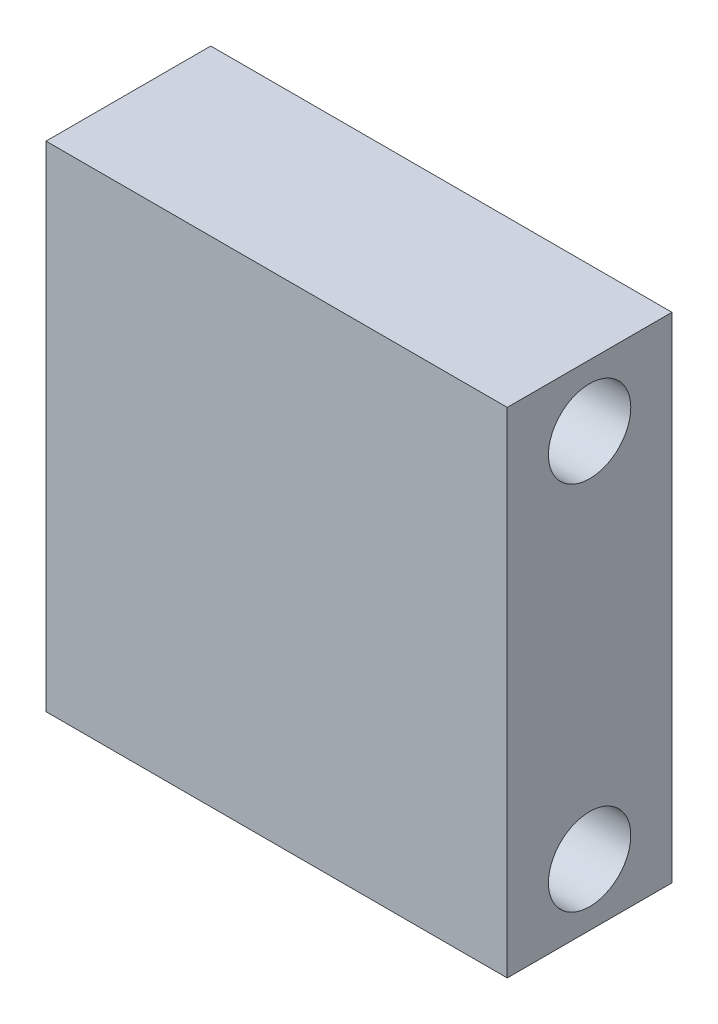
SolidWorks part; units mm, degrees
ref_plane "Front Plane" through (0, 0, 0) normal (0, 0, 1) x (1, 0, 0)
ref_plane "Top Plane" through (0, 0, 0) normal (0, 1, 0) x (1, 0, 0)
ref_plane "Right Plane" through (0, 0, 0) normal (1, 0, 0) x (0, 0, -1)
sketch "Sketch1" plane through (0, 0, 0) normal (1, 0, 0) x (0, 0, -1)
  line L0 (0, -22.5) -> (0, 22.5) construction
  line L1 (-10, 30) -> (10, 30)
  line L2 (-10, 30) -> (-10, -30)
  line L3 (-10, -30) -> (10, -30)
  line L4 (10, 30) -> (10, -30)
  line L5 (-10, 30) -> (10, -30) construction
  line L6 (-10, -30) -> (10, 30) construction
  line L7 (-10, 0) -> (10, 0) construction
  circle A0 centre (0, 22.5) radius 5
  circle A1 centre (0, -22.5) radius 5
  point P0 (0, 0)
  point P12 (0, 0)
  point P14 (4.7815, 23.9619)
  dimension "D3" = 10
  dimension "D1" = 20
  dimension "D2" = 60
  dimension "D4" = 45
extrude "Boss-Extrude1" add sketch "Sketch1" along normal blind 56
sketch "Sketch2" plane through (0, 0, -10) normal (0, 0, 1) x (1, 0, 0)
  line L0 (28, 30) -> (28, -90) construction
  line L1 (56, 30) -> (0, 30) construction
  dimension "D1" = 120
equation "\"X-ROD-SPACING\"=45"
equation "\"Y-ROD-SPACING\"=75"
equation "\"Z-ROD-SPACING\"=17.5"
equation "\"Y-BED-OFFSET\"=0"
equation "\"Y-BED-ROD-INSET\"=3.5"
equation "\"T-SLOT-NUT-FILLET-RADIUS\"=0.25"
equation "\"T-SLOT-SCREW-SHAFT-RADIUS\"=1.75"
equation "\"T-SLOT-SCREW-SHAFT-CUTOUT-LENGTH\"=10.5"
equation "\"T-SLOT-NUT-DEPTH\"=4.2"
equation "\"T-SLOT-NUT-WIDTH\"=3"
equation "\"T-SLOT-NUT-END-DISTANCE\"=8"
equation "\"ACRYLIC-THICKNESS\"=10"
equation "\"ACRYLIC-THICKNESS2\"=4.5"
equation "\"ACRYLIC-TAB-CUTOUT-SIZE\"=\"ACRYLIC-THICKNESS\"+.5"
equation "\"ACRYLIC-TAB-WIDTH\"=\"ACRYLIC-THICKNESS\""
equation "\"ACRYLIC-M3-HOLE\"=3.2"
equation "\"SMOOTHROD-CAP-SCREW-DISTANCE\"=20"
equation "\"FRAME-WIDTH-INNER\"=370"
equation "\"NEMA17-HOLE-SPACING\"=31"
equation "\"NEMA17-CENTRAL-CUTOUT\"=22.5"
equation "\"Z-BRACKET-REACH\"=55"
equation "\"TOP-BRACKET-SPACING\"=40"
equation "\"SMOOTHROD-X-LENGTH\"=350"
equation "\"SMOOTHROD-Y-LENGTH\"=350"
equation "\"SMOOTHROD-Z-LENGTH\"=350"
equation "\"SMOOTHROD-TIGHTENING-HEADROOM\"=1"
equation "\"LEADSCREW-Z-LENGTH\"=300"
equation "\"SCREW-LENGTH-FRAME\"=\"ACRYLIC-THICKNESS\" + 10"
equation "\"SCREW-HEAD-RADIUS\"=6"
equation "\"PRINTED-X-SMOOTHROD-DIAMETER\"=8.2"
equation "\"PRINTED-X-SMOOTHROD-CUTOUT\"=10"
equation "\"PRINTED-X-BASE-HEIGHT\"=10"
equation "\"PRINTED-LM8UU-CUTOUT-SIZE\"=16"
equation "\"PRINTED-LM8UU-CUTOUT-LENGTH\"=24.5"
equation "\"PRINTED-X-IDLER-HEIGHT\"=16"
equation "\"PSU-MOUNTING-WIDTH\"=95"
equation "\"PSU-MOUNTING-HEIGHT\"=177"
equation "\"Y-BELT-TO-ROD-DISTANCE\"=20"
equation "\"D4@Sketch1\"=\"X-ROD-SPACING\""
